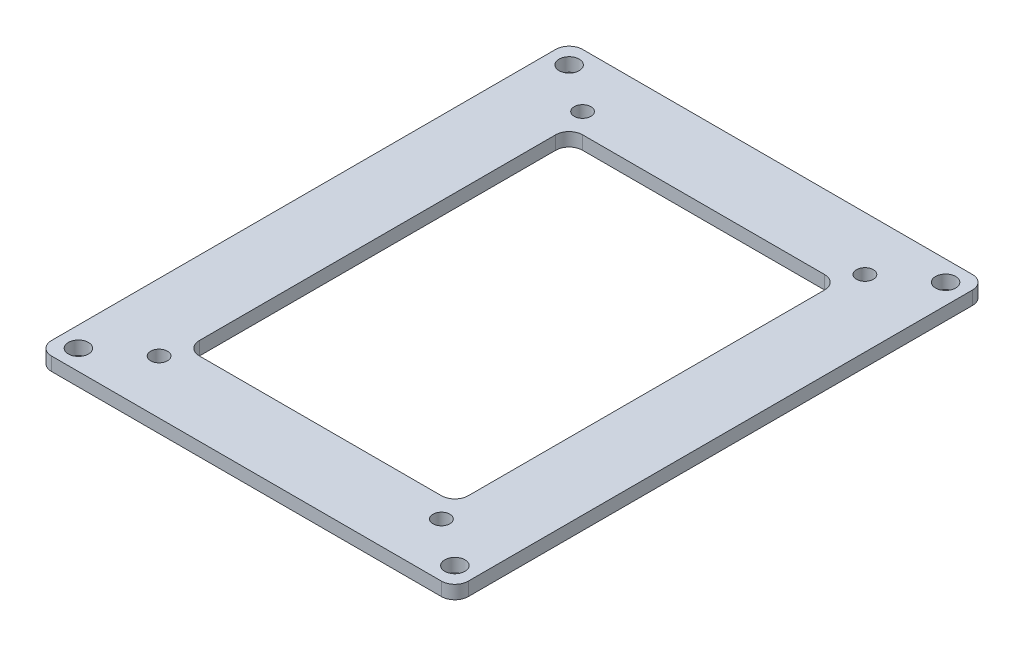
SolidWorks part; units mm, degrees
material "环氧玻璃布层压板"
ref_plane "前视基准面" through (0, 0, 0) normal (0, 0, 1) x (1, 0, 0)
ref_plane "上视基准面" through (0, 0, 0) normal (0, 1, 0) x (1, 0, 0)
ref_plane "右视基准面" through (0, 0, 0) normal (1, 0, 0) x (0, 0, -1)
sketch "草图1" plane through (0, 0, 0) normal (0, 1, 0) x (1, 0, 0)
  line L1 (-21, -31.5) -> (21, -31.5) construction
  line L2 (-21, -31.5) -> (-21, 31.5) construction
  line L3 (-21, 31.5) -> (21, 31.5) construction
  line L4 (21, -31.5) -> (21, 31.5) construction
  line L5 (0, 31.5) -> (0, -31.5) construction
  line L6 (-21, 0) -> (21, 0) construction
  line L7 (-31, -39.5) -> (31, -39.5)
  line L8 (-31, -39.5) -> (-31, 39.5)
  line L9 (-31, 39.5) -> (31, 39.5)
  line L10 (31, -39.5) -> (31, 39.5)
  line L11 (0, 39.5) -> (0, -39.5) construction
  line L12 (-31, 0) -> (31, 0) construction
  circle A0 centre (-21, 31.5) radius 1.25
  circle A1 centre (21, 31.5) radius 1.25
  circle A2 centre (-21, -31.5) radius 1.25
  circle A3 centre (21, -31.5) radius 1.25
  point P0 (0, 0)
  point P4 (0, 0)
  dimension "D5" = 2.5
  dimension "D1" = 63
  dimension "D2" = 42
  dimension "D3" = 8
  dimension "D4" = 10
extrude "凸台-拉伸1" add sketch "草图1" along normal blind 2
sketch "草图2" plane through (0, 2, 0) normal (0, 1, 0) x (1, 0, 0)
  line L0 (31, 39.5) -> (-31, 39.5) construction
  line L1 (-28, -36.5) -> (28, -36.5) construction
  line L2 (-28, -36.5) -> (-28, 36.5) construction
  line L3 (-28, 36.5) -> (28, 36.5) construction
  line L4 (28, -36.5) -> (28, 36.5) construction
  line L5 (0, 36.5) -> (0, -36.5) construction
  line L6 (-28, 0) -> (28, 0) construction
  line L7 (31, -39.5) -> (31, 39.5) construction
  circle A0 centre (28, 36.5) radius 1.4986
  circle A1 centre (-28, 36.5) radius 1.4986
  circle A2 centre (-28, -36.5) radius 1.4986
  circle A3 centre (28, -36.5) radius 1.4986
  point P0 (0, 0)
  dimension "D3" = 2.9972
  dimension "D1" = 3
  dimension "D2" = 3
extrude "切除-拉伸1" cut sketch "草图2" against normal blind 2
sketch "草图3" plane through (0, 2, 0) normal (0, 1, 0) x (1, 0, 0)
  line L1 (-20, -28.5) -> (20, -28.5)
  line L2 (-20, -28.5) -> (-20, 28.5)
  line L3 (-20, 28.5) -> (20, 28.5)
  line L4 (20, -28.5) -> (20, 28.5)
  line L5 (0, 28.5) -> (0, -28.5) construction
  line L6 (-20, 0) -> (20, 0) construction
  circle A0 centre (21, -31.5) radius 1.25 construction
  circle A1 centre (21, 31.5) radius 1.25 construction
  point P0 (0, 0)
  dimension "D1" = 3
  dimension "D2" = 1
extrude "切除-拉伸2" cut sketch "草图3" against normal blind 2
fillet "圆角1" radius 2 8 edges at (-31, 1, 39.5) (-31, 1, -39.5) (31, 1, -39.5) (31, 1, 39.5) (-20, 1, -28.5) (20, 1, -28.5) (20, 1, 28.5) (-20, 1, 28.5)
